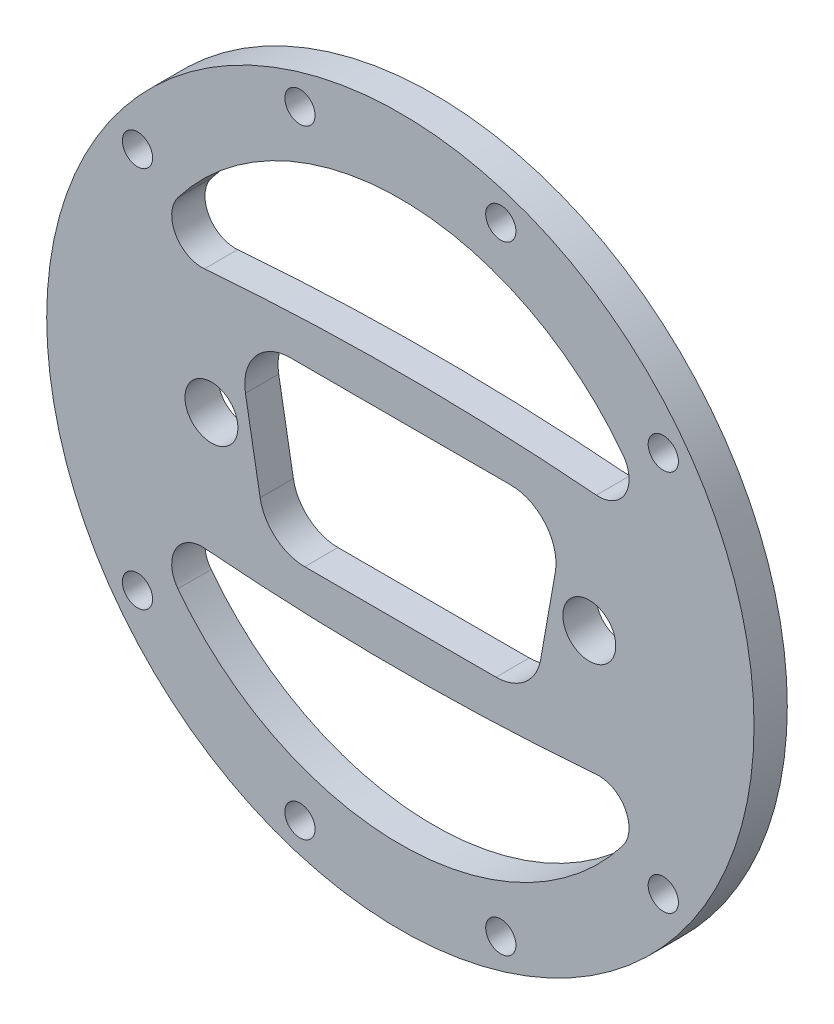
SolidWorks part; units mm, degrees
material "2014 Legierung"
ref_plane "Vorne" through (0, 0, 0) normal (0, 0, 1) x (1, 0, 0)
ref_plane "Oben" through (0, 0, 0) normal (0, 1, 0) x (1, 0, 0)
ref_plane "Rechts" through (0, 0, 0) normal (1, 0, 0) x (0, 0, -1)
sketch "Skizze1" plane through (0, 0, 0) normal (0, 0, 1) x (1, 0, 0)
  line L0 (-12.9673, 8) -> (12.9673, 8) construction
  line L2 (0, 0) -> (33.7788, 0) construction
  line L4 (-12.9673, -8) -> (12.9673, -8) construction
  line L5 (-6.6439, 20.4477) -> (0, 0) construction
  line L6 (-12.9673, 8) -> (12.9673, 8) construction
  line L7 (0, 0) -> (0, 25.2877) construction
  line L8 (-12.9673, -8) -> (12.9673, -8) construction
  circle A0 centre (0, 0) radius 23.4
  arc A1 (14.7209, 11.2047) -> (-14.7209, 11.2047) centre (0, 0) ccw
  arc A2 (-14.7209, -11.2047) -> (14.7209, -11.2047) centre (0, 0) ccw
  arc A3 (-12.9673, 8) -> (-14.7209, 11.2047) centre (-13.1294, 9.9934) cw
  arc A4 (12.9673, 8) -> (14.7209, 11.2047) centre (13.1294, 9.9934) ccw
  arc A5 (-12.9673, -8) -> (-14.7209, -11.2047) centre (-13.1294, -9.9934) ccw
  arc A6 (12.9673, -8) -> (14.7209, -11.2047) centre (13.1294, -9.9934) cw
  circle A7 centre (6.6439, 20.4477) radius 1
  circle A8 centre (17.3939, 12.6374) radius 1
  circle A10 centre (17.3939, -12.6374) radius 1
  arc A11 (-12.9673, 8) -> (12.9673, 8) centre (0, -151.4737) cw
  arc A12 (-12.9673, -8) -> (12.9673, -8) centre (0, 151.4737) ccw
  circle A13 centre (-6.6439, 20.4477) radius 1
  circle A14 centre (6.6439, -20.4477) radius 1
  circle A15 centre (-6.6439, -20.4477) radius 1
  circle A16 centre (-17.3939, -12.6374) radius 1
  circle A18 centre (-17.3939, 12.6374) radius 1
  circle A47 centre (-21.5, 0) radius 1 [skipped]
  circle A48 centre (21.5, 0) radius 1 [skipped]
  dimension "D1" = 37
  dimension "D2" = 46.8
  dimension "D3" = 2
  dimension "D6" = 160
  dimension "D7" = 21.5
  dimension "D8" = 2
  dimension "D5" = 16
  dimension "D9" = 18
extrude "Linear austragen1" add sketch "Skizze1" along normal blind 2.2
sketch "Skizze3" plane through (0, 0, 2.2) normal (0, 0, 1) x (1, 0, 0)
  line L0 (0, 0) -> (0, 13.9221) construction
  line L1 (-7.2956, 5.75) -> (7.2956, 5.75)
  line L2 (-10.25, 2.2291) -> (-9.2802, -3.2709)
  line L3 (-6.3258, -5.75) -> (6.3258, -5.75)
  line L4 (10.25, 2.2291) -> (9.2802, -3.2709)
  line L5 (0, 0) -> (3.5223, 0) construction
  circle A0 centre (12.5, 0) radius 1.75
  circle A1 centre (-12.5, 0) radius 1.75
  arc A2 (7.2956, 5.75) -> (10.25, 2.2291) centre (7.2956, 2.75) cw
  arc A3 (6.3258, -5.75) -> (9.2802, -3.2709) centre (6.3258, -2.75) ccw
  arc A4 (-9.2802, -3.2709) -> (-6.3258, -5.75) centre (-6.3258, -2.75) ccw
  arc A5 (-7.2956, 5.75) -> (-10.25, 2.2291) centre (-7.2956, 2.75) ccw
  dimension "D1" = 3.5
  dimension "D5" = 3
  dimension "D2" = 25
  dimension "D3" = 80
  dimension "D4" = 11.5
  dimension "D6" = 20.5
extrude "Schnitt-Linear austragen3" cut sketch "Skizze3" against normal through all
